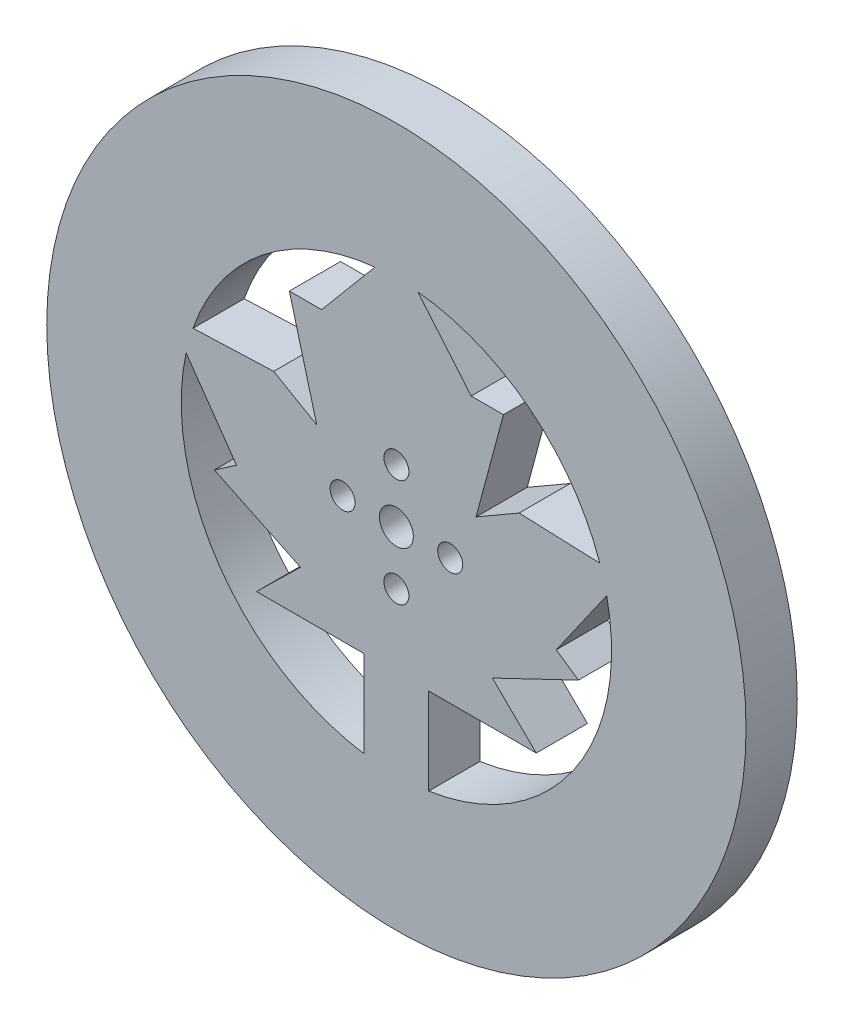
SolidWorks part; units mm, degrees
ref_plane "Front Plane" through (0, 0, 0) normal (0, 0, 1) x (1, 0, 0)
ref_plane "Top Plane" through (0, 0, 0) normal (0, 1, 0) x (1, 0, 0)
ref_plane "Right Plane" through (0, 0, 0) normal (1, 0, 0) x (0, 0, -1)
sketch "Sketch1" plane through (0, 0, 0) normal (0, 0, 1) x (1, 0, 0)
  circle A0 centre (0, 0) radius 41.275
  circle A2 centre (-6.35, 0) radius 1.4732
  circle A3 centre (0, 6.35) radius 1.4732
  circle A4 centre (6.35, 0) radius 1.4732
  circle A5 centre (0, -6.35) radius 1.4732
  circle A6 centre (0, 0) radius 2
  dimension "D1" = 82.55
  dimension "D3" = 2.9464
  dimension "D5" = 4
  dimension "D4" = 6.35
extrude "Boss-Extrude1" add sketch "Sketch1" along normal blind 6.0452
sketch "Sketch2" plane through (0, 0, 6.0452) normal (0, 0, 1) x (1, 0, 0)
  line L0 (0, 25.4) -> (0, -25.4) construction
  line L1 (8.8271, 17.78) -> (2.54, 25.2727)
  line L2 (8.8271, 17.78) -> (12.6371, 17.78)
  line L3 (12.6371, 17.78) -> (9.4043, 5.715)
  line L4 (9.4043, 5.715) -> (14.4843, 8.6479)
  line L5 (14.4843, 8.6479) -> (24.0093, 8.2894)
  line L6 (18.8681, -3.1406) -> (24.8262, 5.3684)
  line L7 (18.8681, -3.1406) -> (21.4871, -4.9356)
  line L8 (21.4871, -4.9356) -> (11.3271, -9.7979)
  line L9 (11.3271, -9.7979) -> (16.51, -14.8779)
  line L10 (16.51, -14.8779) -> (3.81, -14.8779)
  line L11 (3.81, -14.8779) -> (3.81, -25.1126)
  line L12 (-3.81, -14.8779) -> (-3.81, -25.1126)
  line L13 (-16.51, -14.8779) -> (-3.81, -14.8779)
  line L14 (-11.3271, -9.7979) -> (-16.51, -14.8779)
  line L15 (-21.4871, -4.9356) -> (-11.3271, -9.7979)
  line L16 (-18.8681, -3.1406) -> (-21.4871, -4.9356)
  line L17 (-18.8681, -3.1406) -> (-24.8262, 5.3684)
  line L18 (-14.4843, 8.6479) -> (-24.0093, 8.2894)
  line L19 (-9.4043, 5.715) -> (-14.4843, 8.6479)
  line L20 (-12.6371, 17.78) -> (-9.4043, 5.715)
  line L21 (-8.8271, 17.78) -> (-12.6371, 17.78)
  line L22 (-8.8271, 17.78) -> (-2.54, 25.2727)
  arc A0 (3.81, -25.1126) -> (24.8262, 5.3684) centre (0, 0) ccw
  arc A1 (-24.8262, 5.3684) -> (-3.81, -25.1126) centre (0, 0) ccw
  arc A2 (-2.54, 25.2727) -> (-24.0093, 8.2894) centre (0, 0) ccw
  arc A3 (24.0093, 8.2894) -> (2.54, 25.2727) centre (0, 0) ccw
  circle A4 centre (0, 0) radius 25.4 construction
  dimension "D1" = 50.8
  dimension "D2" = 7.62
  dimension "D3" = 3.81
  dimension "D4" = 2.54
  dimension "D5" = 12.065
  dimension "D6" = 75
  dimension "D7" = 5.08
  dimension "D8" = 45
  dimension "D9" = 9.525
  dimension "D10" = 8.509
  dimension "D11" = 2.921
  dimension "D12" = 3.175
  dimension "D13" = 10.16
  dimension "D14" = 60
  dimension "D15" = 5.08
  dimension "D16" = 12.7
  dimension "D17" = 70
  dimension "D18" = 3.81
  dimension "D19" = 35
  dimension "D20" = 40
extrude "Cut-Extrude3" cut sketch "Sketch2" against normal through all
